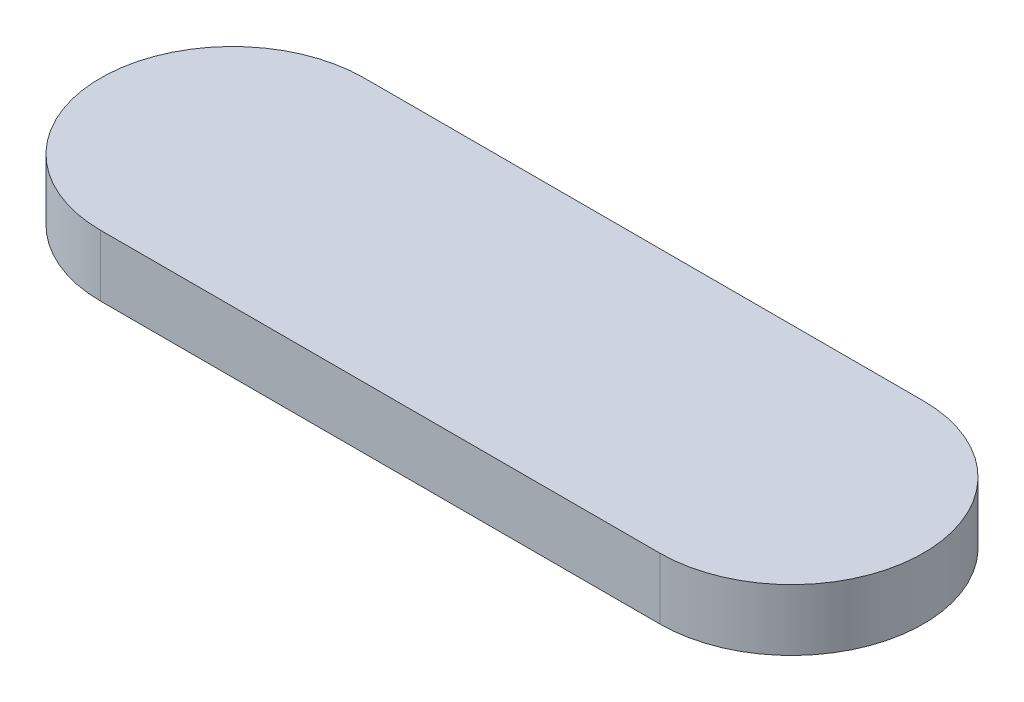
SolidWorks part; units mm, degrees
ref_plane "前视基准面" through (0, 0, 0) normal (0, 0, 1) x (1, 0, 0)
ref_plane "上视基准面" through (0, 0, 0) normal (0, 1, 0) x (1, 0, 0)
ref_plane "右视基准面" through (0, 0, 0) normal (1, 0, 0) x (0, 0, -1)
sketch "草图1" plane through (0, 0, 0) normal (0, 1, 0) x (1, 0, 0)
  line L0 (-11.2076, 2.9789) -> (13.3924, 2.9789)
  line L2 (-11.2076, -8.6211) -> (13.3924, -8.6211)
  arc A0 (-11.2076, 2.9789) -> (-11.2076, -8.6211) centre (-11.2076, -2.8211) ccw
  arc A1 (13.3924, -8.6211) -> (13.3924, 2.9789) centre (13.3924, -2.8211) ccw
  dimension "D1" = 11.6
  dimension "D2" = 11.6
  dimension "D3" = 24.6
extrude "凸台-拉伸1" add sketch "草图1" along normal blind 2.7
